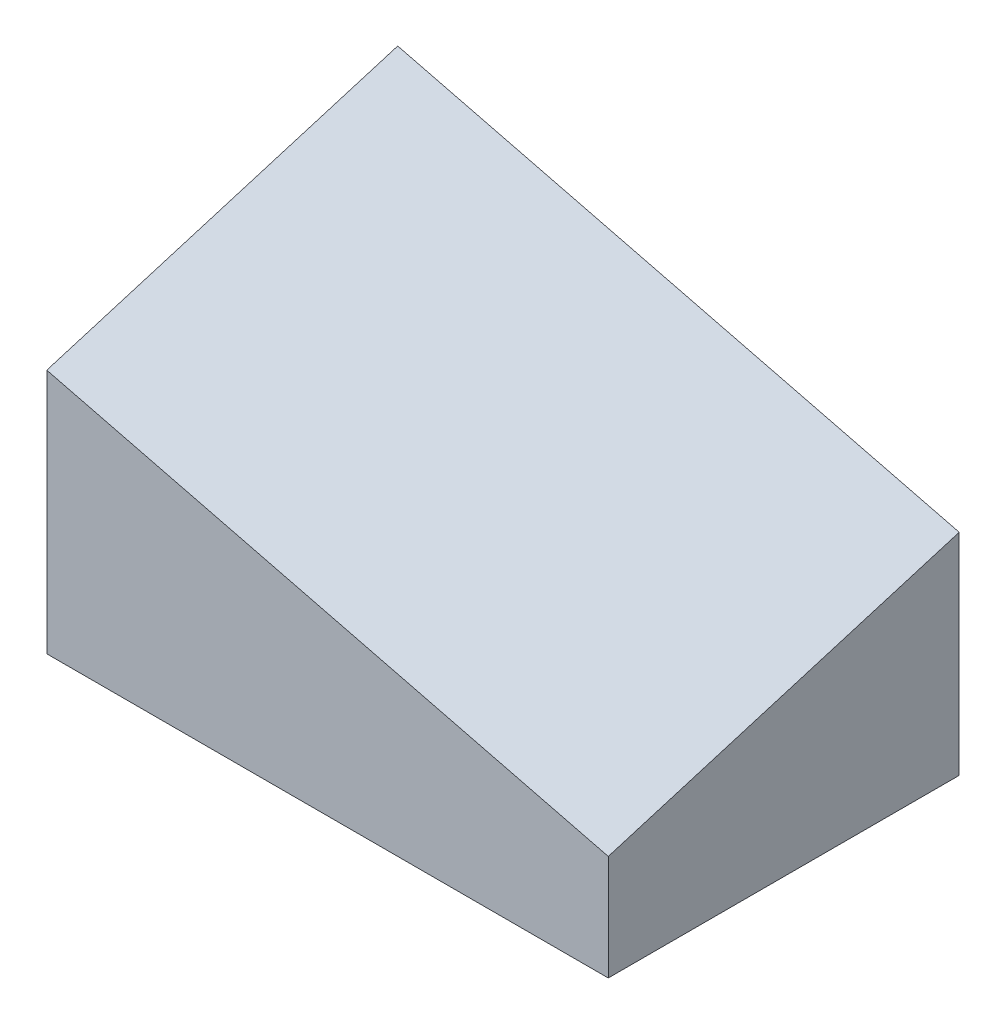
SolidWorks part; units mm, degrees
material "___"
ref_plane "Front Plane" through (0, 0, 0) normal (0, 0, 1) x (1, 0, 0)
ref_plane "Top Plane" through (0, 0, 0) normal (0, 1, 0) x (1, 0, 0)
ref_plane "Right Plane" through (0, 0, 0) normal (1, 0, 0) x (0, 0, -1)
sketch "Sketch7" plane through (0, 0, 0) normal (0, 1, 0) x (1, 0, 0)
  line L1 (-2, -1.25) -> (2, -1.25)
  line L2 (-2, -1.25) -> (-2, 1.25)
  line L3 (-2, 1.25) -> (2, 1.25)
  line L4 (2, -1.25) -> (2, 1.25)
  line L5 (-2, -1.25) -> (2, 1.25) construction
  line L6 (-2, 1.25) -> (2, -1.25) construction
  point P0 (0, 0)
  dimension "D1" = 4
  dimension "D2" = 2.5
extrude "Boss-Extrude4" add sketch "Sketch7" along normal blind 2.5
sketch3d "3DSketch1"
  line L0 (-2, 2.5, -1.25) -> (-2, 1.75, 1.25)
  line L2 (-2, 1.75, 1.25) -> (2, 0.75, 1.25)
  line L3 (2, 2.5, 1.25) -> (2, 0, 1.25) construction
  line L4 (2, 0.75, 1.25) -> (2, 1.5, -1.25)
  line L5 (2, 2.5, -1.25) -> (2, 0, -1.25) construction
  line L6 (2, 1.5, -1.25) -> (-2, 2.5, -1.25)
  line L7 (2, 0, 1.25) -> (2, 0, -1.25) construction
  line L8 (-2, 2.5, 1.25) -> (-2, 0, 1.25) construction
  point P11 (-1.6943, 1.8183, 1.3161)
  dimension "D1" = 0.75
  dimension "D2" = 0.75
  dimension "D3" = 1.5
extrude "Cut-Extrude1" cut sketch "3DSketch1" along direction (0, -1, 0) on the side against the normal blind 2.5
